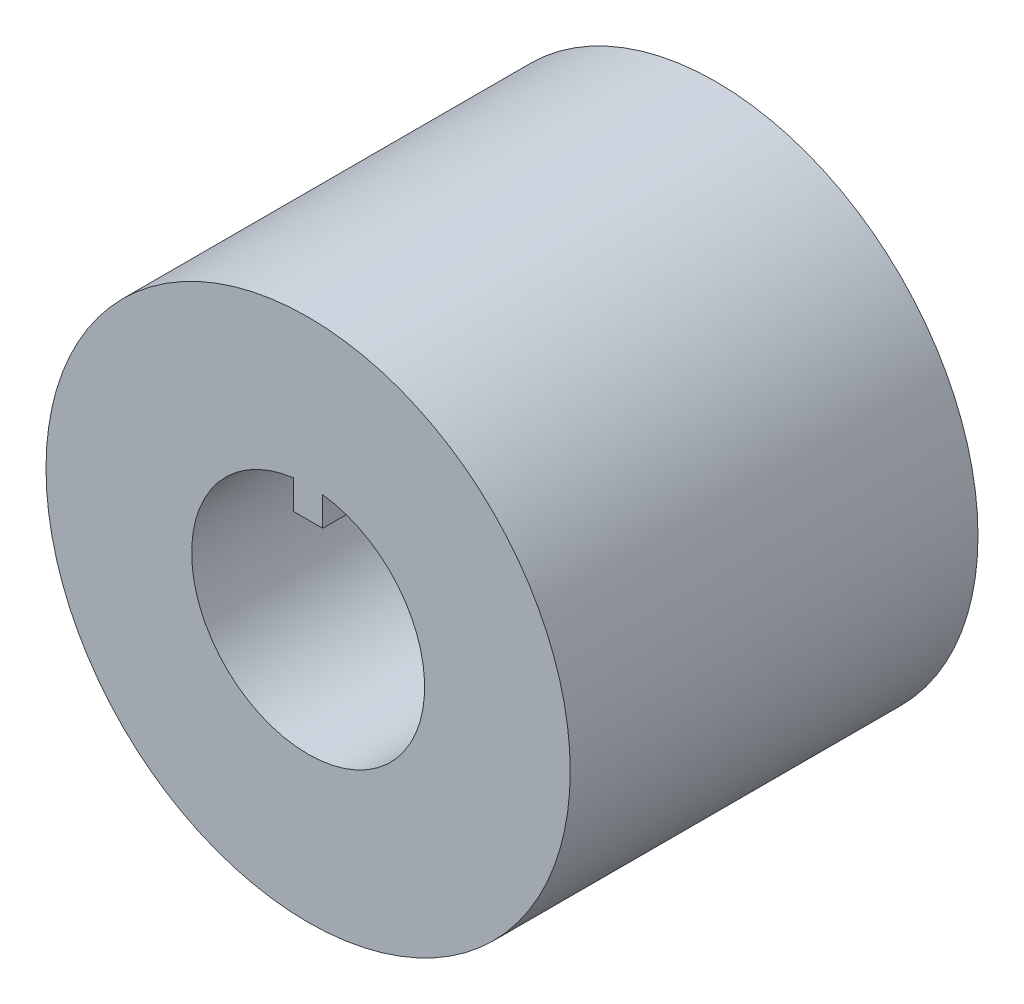
SolidWorks part; units mm, degrees
ref_plane "Plan de face" through (0, 0, 0) normal (0, 0, 1) x (1, 0, 0)
ref_plane "Plan de dessus" through (0, 0, 0) normal (0, 1, 0) x (1, 0, 0)
ref_plane "Plan de droite" through (0, 0, 0) normal (1, 0, 0) x (0, 0, -1)
sketch "Esquisse1" plane through (0, 0, 0) normal (0, 0, 1) x (1, 0, 0)
  line L0 (0, -1000) -> (0, 29.6863) construction
  line L1 (-5, -953.2287) -> (-5, 49046.7713) construction
  line L2 (5, -957.3662) -> (5, 49042.6338) construction
  line L3 (-5, 39.6863) -> (-5, 29.6863)
  line L4 (-5, 29.6863) -> (5, 29.6863)
  line L5 (5, 29.6863) -> (4.938, 39.694)
  arc A0 (-5, 39.6863) -> (4.938, 39.694) centre (0, 0) ccw
  circle A1 centre (0, 0) radius 90
  point P8 (-5, 39.6863)
  point P10 (4.938, 39.694)
  dimension "D1" = 80
  dimension "D6" = 180
  dimension "D2" = 5
  dimension "D3" = 5
  dimension "D4" = 10
  dimension "D5" = 10
extrude "Boss.-Extru.1" add sketch "Esquisse1" along normal blind 140
